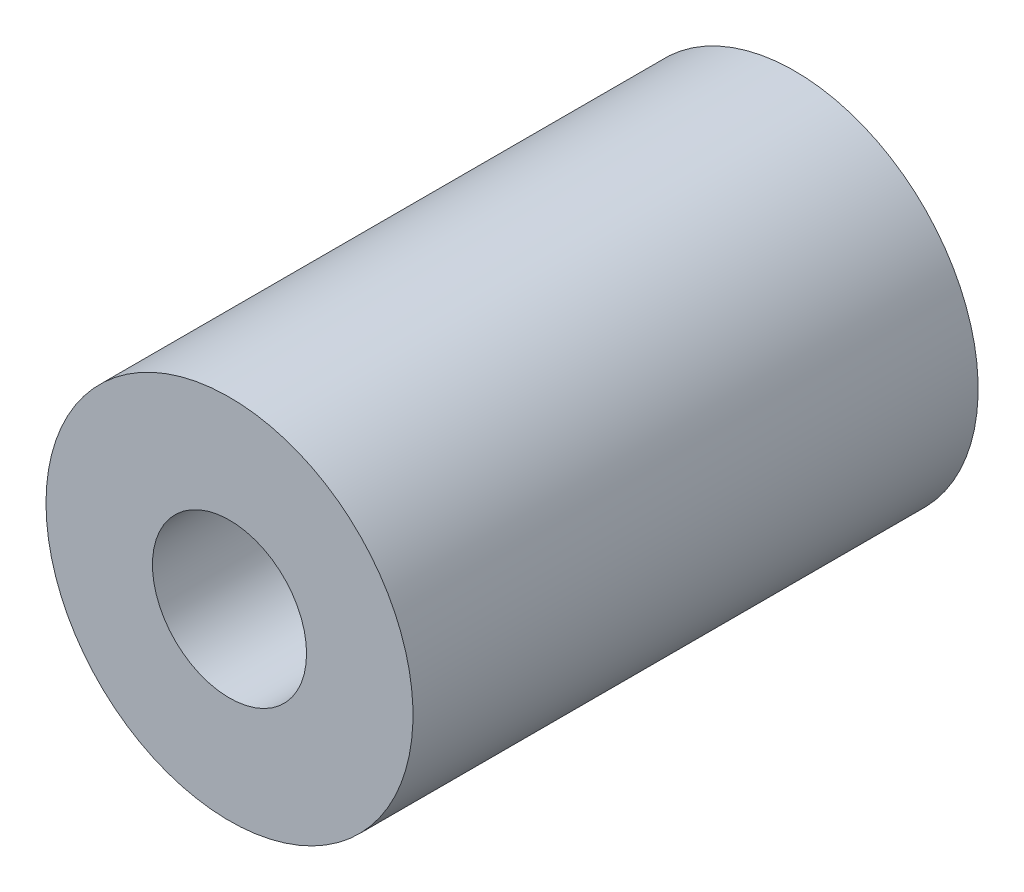
SolidWorks part; units mm, degrees
material "1060 合金"
ref_plane "正面" through (0, 0, 0) normal (0, 0, 1) x (1, 0, 0)
ref_plane "平面" through (0, 0, 0) normal (0, 1, 0) x (1, 0, 0)
ref_plane "右側面" through (0, 0, 0) normal (1, 0, 0) x (0, 0, -1)
sketch "ｽｹｯﾁ1" plane through (0, 0, 0) normal (0, 0, 1) x (1, 0, 0)
  circle A0 centre (0, 0) radius 5
  dimension "D1" = 10
extrude "ﾎﾞｽ - 押し出し1" add sketch "ｽｹｯﾁ1" along normal blind 15.4
sketch "ｽｹｯﾁ2" plane through (0, 0, 15.4) normal (0, 0, 1) x (1, 0, 0)
  circle A0 centre (0, 0) radius 2.1
  dimension "D1" = 4.2
extrude "ｶｯﾄ - 押し出し1" cut sketch "ｽｹｯﾁ2" against normal blind 10
ref_plane "平面1" through (0, 0, 7.7) normal (0, 0, 1) x (1, 0, 0)
mirror "ﾐﾗｰ1" about plane through (0, 0, 7.7) normal (0, 0, 1) of "ｶｯﾄ - 押し出し1"
